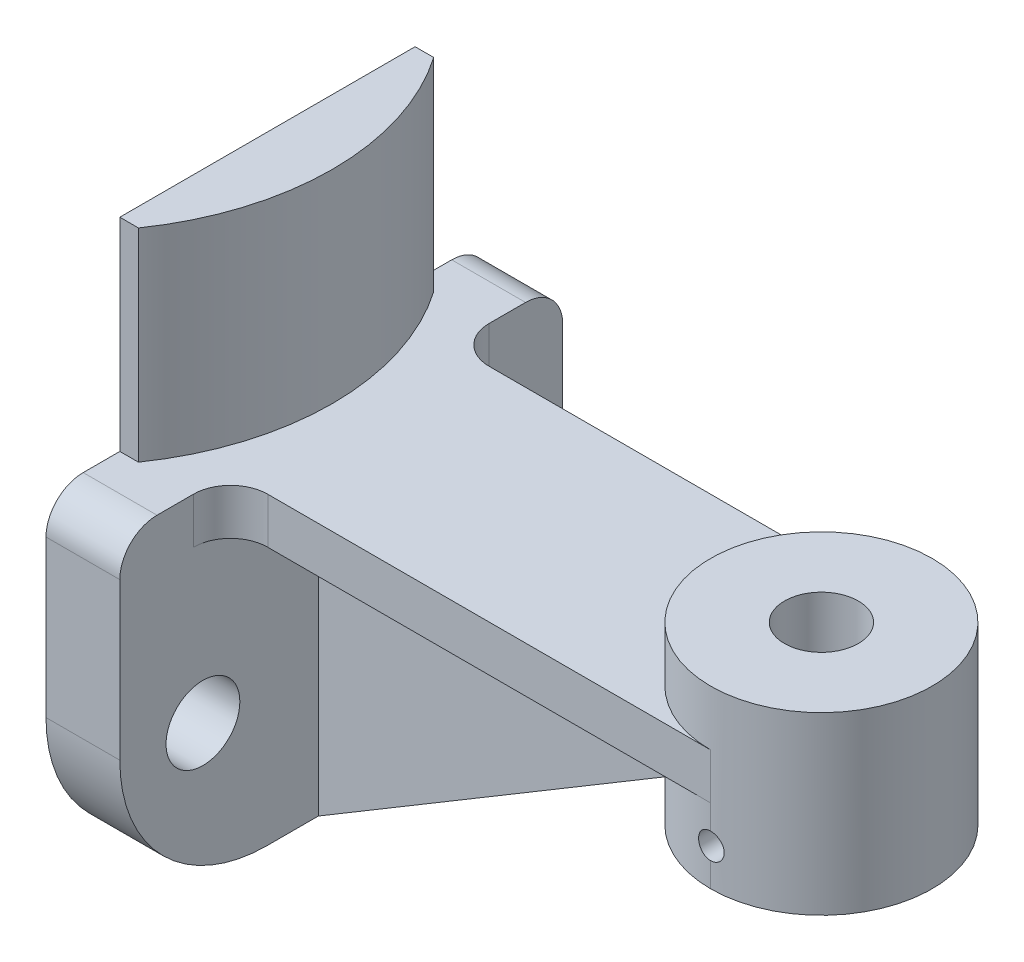
SolidWorks part; units mm, degrees
other "DetailItem1"
other "DetailItem2"
other "DetailItem3"
ref_plane "Front" through (0, 0, 0) normal (0, 0, 1) x (1, 0, 0)
ref_plane "Top" through (0, 0, 0) normal (0, 1, 0) x (1, 0, 0)
ref_plane "Right" through (0, 0, 0) normal (1, 0, 0) x (0, 0, -1)
sketch "Sketch1" plane through (0, 0, 0) normal (1, 0, 0) x (0, 0, -1)
  line L0 (0, 0) -> (76.2, 0)
  line L1 (0, 0) -> (0, 58.7)
  line L2 (76.2, 58.7) -> (0, 58.7)
  line L3 (76.2, 58.7) -> (76.2, 0)
  dimension "D1" = 76.2
  dimension "D2" = 58.7
extrude "Base-Extrude" add sketch "Sketch1" along normal blind 12.7
sketch "Sketch2" plane through (12.7, 0, 0) normal (1, 0, 0) x (0, 0, -1)
  line L0 (19.05, 58.7) -> (57.15, 58.7)
  line L1 (19.05, 58.7) -> (19.05, 50.8)
  line L2 (57.15, 50.8) -> (19.05, 50.8)
  line L3 (57.15, 50.8) -> (57.15, 58.7)
  line L4 (76.2, 58.7) -> (0, 58.7) construction
  line L5 (38.1, 58.7) -> (38.1, 0) construction
  line L6 (0, 0) -> (76.2, 0) construction
  dimension "D1" = 7.9
  dimension "D2" = 38.1
extrude "Boss-Extrude3" add sketch "Sketch2" along normal offset from surface (82.6 mm away) 95.3
ref_plane "Plane4" through (0, 68.2, 0) normal (0, 1, 0) x (-1, 0, 0)
sketch "Sketch4" plane through (0, 68.2, 0) normal (0, 1, 0) x (-1, 0, 0)
  line L0 (-95.3, -57.15) -> (-95.3, -19.05) construction
  circle A0 centre (-95.3, -38.1) radius 19.05
extrude "Boss-Extrude4" add sketch "Sketch4" against normal blind 30.2
sketch "Sketch5" plane through (0, 58.7, 0) normal (0, 1, 0) x (-1, 0, 0)
  line L0 (0, -63.5) -> (-3.2, -63.5)
  line L1 (0, -63.5) -> (0, -12.7)
  line L2 (-3.2, -12.7) -> (0, -12.7)
  line L4 (0, -76.2) -> (0, 0) construction
  arc A0 (-3.2, -12.7) -> (-3.2, -63.5) centre (33.3389, -38.1) ccw
  point P6 (0, -38.1)
  dimension "D3" = 44.5
  dimension "D1" = 50.8
  dimension "D2" = 3.2
extrude "Boss-Extrude5" add sketch "Sketch5" along normal blind 34.9
sketch "Sketch6" plane through (0, 0, 0) normal (1, 0, 0) x (0, 0, -1)
  line L0 (63.5, 93.6) -> (12.7, 93.6) construction
  line L1 (0, 0) -> (76.2, 0) construction
  point P0 (38.1, 93.6)
  point P1 (38.1, 0)
sketch "Sketch7" plane through (0, 0, 0) normal (0, 1, 0) x (1, 0, 0)
  line L0 (12.7, 0) -> (12.7, 76.2) construction
  point P0 (12.7, 38.1)
ref_plane "Plane5" through (0, 0, -38.1) normal (0, 0, -1) x (-1, 0, 0)
sketch "Sketch8" plane through (0, 0, -38.1) normal (0, 0, -1) x (-1, 0, 0)
  line L0 (-12.7, 0) -> (-95.3, 49.391)
  line L2 (-12.7, 50.8) -> (-12.7, 0)
  line L3 (-95.3, 50.8) -> (-12.7, 50.8) construction
  line L4 (-95.3, 50.8) -> (-12.7, 50.8)
  line L5 (-95.3, 50.8) -> (-95.3, 49.391)
  line L6 (-95.3, 50.8) -> (-95.3, 58.7) construction
  point P0 (-76.25, 38)
extrude "Boss-Extrude7" add sketch "Sketch8" along normal mid plane 7.9
sketch "Sketch9" plane through (12.7, 0, 0) normal (1, 0, 0) x (0, 0, -1)
  line L0 (19.05, 58.7) -> (0, 58.7) construction
  line L1 (14.3, 23.8) -> (61.9, 23.8) construction
  line L2 (38.1, 23.8) -> (38.1, 0) construction
  line L3 (42.05, 0) -> (34.15, 0) construction
  circle A0 centre (14.3, 23.8) radius 6.35
  circle A1 centre (61.9, 23.8) radius 6.35
  dimension "D1" = 12.7
  dimension "D2" = 34.9
  dimension "D3" = 47.6
extrude "Cut-Extrude1" cut sketch "Sketch9" against normal through all
cosmetic thread "Cosmetic Thread1" parameters "D2"=15.2
sketch "Sketch10" plane through (0, 68.2, 0) normal (0, 1, 0) x (-1, 0, 0)
  circle A0 centre (-95.3, -38.1) radius 6.35
  circle A1 centre (-95.3, -38.1) radius 19.05 construction
  dimension "D1" = 12.7
extrude "Cut-Extrude2" cut sketch "Sketch10" against normal through all
sketch "Sketch11" plane through (0, 0, -38.1) normal (0, 0, -1) x (-1, 0, 0)
  line L0 (-101.65, 38) -> (-88.95, 38) construction
  circle A0 centre (-95.3, 44.4) radius 2.2
  dimension "D1" = 4.4
  dimension "D2" = 6.4
extrude "Cut-Extrude3" cut sketch "Sketch11" against normal through all and the other way through all
fillet "Fillet1" radius 6.4 6 edges at (6.35, 58.7, -76.2) (6.35, 58.7, 0)
fillet "Fillet2" radius 25.4 2 edges at (6.35, 0, 0) (6.35, 0, -76.2)
fillet "Fillet4" [suppressed] radius 1.5
fillet "Fillet5" [suppressed] radius 1.5
fillet "Fillet6" [suppressed] radius 1.5
fillet "Fillet7" [suppressed] radius 1.5
fillet "Fillet10" [suppressed] radius 1.5
fillet "Fillet11" [suppressed] radius 1.5
